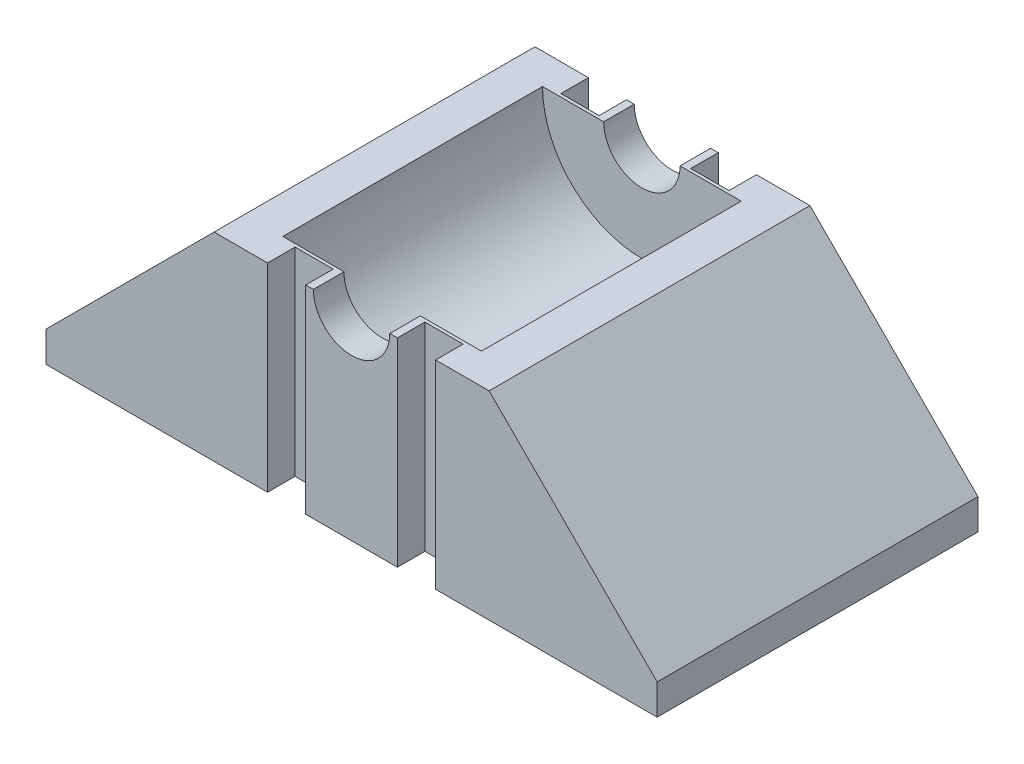
SolidWorks part; units mm, degrees
ref_plane "Płaszczyzna przednia" through (0, 0, 0) normal (0, 0, 1) x (1, 0, 0)
ref_plane "Płaszczyzna górna" through (0, 0, 0) normal (0, 1, 0) x (1, 0, 0)
ref_plane "Płaszczyzna prawa" through (0, 0, 0) normal (1, 0, 0) x (0, 0, -1)
sketch "Sketch5" plane through (0, 0, 0) normal (0, 0, 1) x (1, 0, 0)
  line L1 (-40, 13) -> (0, 13)
  line L2 (-40, 13) -> (-40, 0)
  line L3 (-40, 0) -> (0, 0)
  line L4 (0, 13) -> (0, 0)
  dimension "D1" = 40
  dimension "D2" = 13
extrude "Boss-Extrude2" add sketch "Sketch5" along normal blind 10.5
sketch "Sketch6" plane through (0, 0, 0) normal (0, 0, -1) x (-1, 0, 0)
  line L0 (0, 13) -> (40, 13) construction
  circle A0 centre (20, 13) radius 6.5
  dimension "D1" = 13
extrude "Cut-Extrude4" cut sketch "Sketch6" against normal blind 8.5
sketch "Sketch7" plane through (0, 0, 10.5) normal (0, 0, 1) x (1, 0, 0)
  line L0 (0, 13) -> (-40, 13) construction
  circle A0 centre (-20, 13) radius 2.5
  dimension "D1" = 5
extrude "Cut-Extrude5" cut sketch "Sketch7" against normal blind 4.5 contours A0
mirror "Mirror5" about plane through (0, 0, 0) normal (0, 0, 1) of "Cut-Extrude4", "Cut-Extrude5", "Boss-Extrude2"
sketch "Sketch8" plane through (0, 0, 0) normal (0, -1, 0) x (1, 0, 0)
  line L0 (-40, 0) -> (0, 0) construction
  line L1 (-20, 10.5) -> (-20, -10.5) construction
  line L2 (-40, 10.5) -> (-40, -10.5) construction
  line L3 (0, 10.5) -> (0, -10.5) construction
  line L4 (-40, -10.5) -> (0, -10.5) construction
  line L5 (-40, 10.5) -> (0, 10.5) construction
  circle A0 centre (-31, 5.5) radius 4
  circle A1 centre (-9, 5.5) radius 4
  circle A2 centre (-9, -5.5) radius 4
  circle A3 centre (-31, -5.5) radius 4
  point P14 (0, 0)
  dimension "D1" = 8
  dimension "D2" = 5
  dimension "D3" = 9
extrude "Cut-Extrude6" cut sketch "Sketch8" against normal blind 5
chamfer "Chamfer8" distance 11 angle 45 2 edges at (-40, 13, 0) (0, 13, 0)
sketch "Sketch9" plane through (0, 0, 0) normal (0, -1, 0) x (1, 0, 0)
  line L0 (-20, 10.5) -> (-20, -10.5) construction
  line L1 (-40, 0) -> (0, 0) construction
  line L3 (-40, 10.5) -> (0, 10.5) construction
  line L4 (-40, 10.5) -> (-40, -10.5) construction
  line L5 (-40, -10.5) -> (0, -10.5) construction
  line L6 (0, 10.5) -> (0, -10.5) construction
  line L7 (-14.5, 8.7) -> (-17, 8.7)
  line L8 (-25.5, 10.5) -> (-23, 10.5)
  line L9 (-25.5, 10.5) -> (-25.5, 8.7)
  line L10 (-25.5, 8.7) -> (-23, 8.7)
  line L11 (-23, 10.5) -> (-23, 8.7)
  line L12 (-17, 10.5) -> (-17, 8.7)
  line L13 (-14.5, 10.5) -> (-17, 10.5)
  line L14 (-14.5, 10.5) -> (-14.5, 8.7)
  line L15 (-14.5, -10.5) -> (-14.5, -8.7)
  line L16 (-14.5, -10.5) -> (-17, -10.5)
  line L17 (-17, -10.5) -> (-17, -8.7)
  line L18 (-14.5, -8.7) -> (-17, -8.7)
  line L19 (-25.5, -8.7) -> (-23, -8.7)
  line L20 (-23, -10.5) -> (-23, -8.7)
  line L21 (-25.5, -10.5) -> (-23, -10.5)
  line L22 (-25.5, -10.5) -> (-25.5, -8.7)
  dimension "D1" = 2.5
  dimension "D2" = 1.8
  dimension "D3" = 3
extrude "Cut-Extrude7" cut sketch "Sketch9" against normal blind 15
